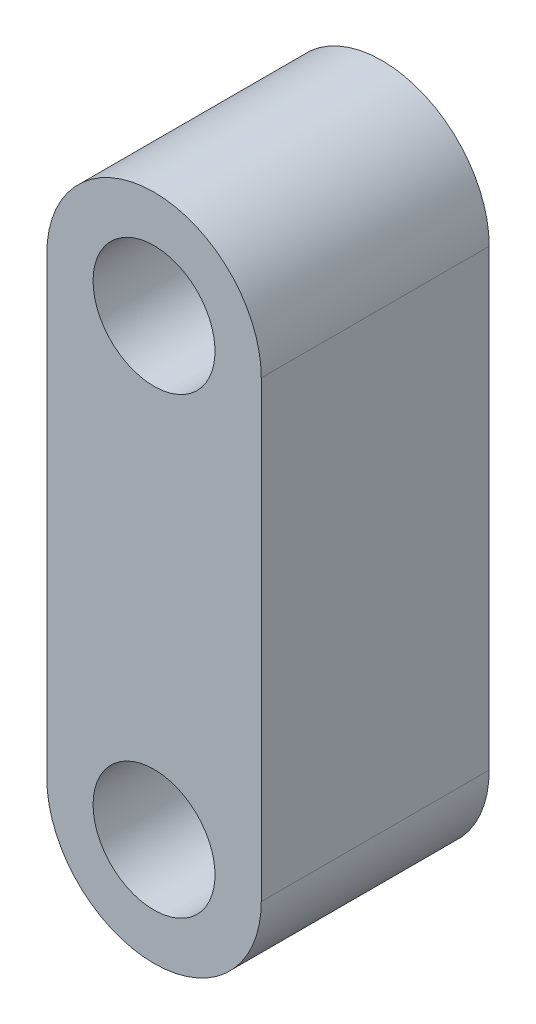
SolidWorks part; units mm, degrees
ref_plane "Front Plane" through (0, 0, 0) normal (0, 0, 1) x (1, 0, 0)
ref_plane "Top Plane" through (0, 0, 0) normal (0, 1, 0) x (1, 0, 0)
ref_plane "Right Plane" through (0, 0, 0) normal (1, 0, 0) x (0, 0, -1)
sketch "Sketch1" plane through (0, 0, 0) normal (0, 0, 1) x (1, 0, 0)
  line L0 (0, -18.9531) -> (0, 18.9531) construction
  line L1 (-8.9631, -18.9531) -> (-8.9631, 18.9531)
  line L2 (8.9631, -18.9531) -> (8.9631, 18.9531)
  arc A0 (-8.9631, -18.9531) -> (8.9631, -18.9531) centre (0, -18.9531) ccw
  arc A1 (8.9631, 18.9531) -> (-8.9631, 18.9531) centre (0, 18.9531) ccw
  circle A2 centre (0, 18.9531) radius 5.0952
  circle A3 centre (0, -18.9531) radius 5.0952
  point P2 (0, 0)
  dimension "D1" = 10.1905
  dimension "D2" = 10.1905
extrude "Boss-Extrude1" add sketch "Sketch1" along normal blind 19.05
equation "\"Pdia\"= 0.4012in"
equation "\"Shaftdia\"= 0.4in"
